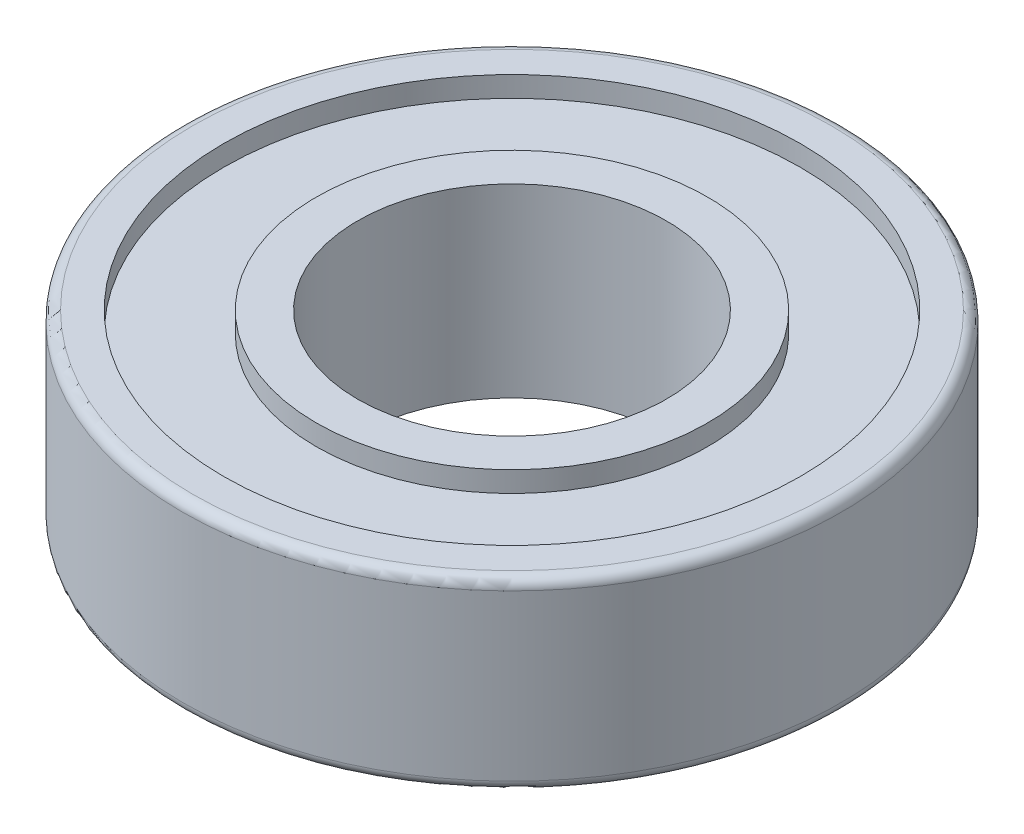
SolidWorks part; units mm, degrees
ref_plane "Plan de face" through (0, 0, 0) normal (0, 0, 1) x (1, 0, 0)
ref_plane "Plan de dessus" through (0, 0, 0) normal (0, 1, 0) x (1, 0, 0)
ref_plane "Plan de droite" through (0, 0, 0) normal (1, 0, 0) x (0, 0, -1)
ref_axis "Axe1" through (0, 4.95, 0) along (0, -1, 0)
sketch "Disque_Intérieur" plane through (0, 0, 0) normal (0, 0, 1) x (1, 0, 0)
  line L1 (7.5, -4.5) -> (9.5, -4.5)
  line L2 (7.5, -4.5) -> (7.5, 4.5)
  line L3 (7.5, 4.5) -> (9.5, 4.5)
  line L4 (9.5, -4.5) -> (9.5, 4.5)
  line L5 (7.5, -4.5) -> (9.5, 4.5) construction
  line L6 (7.5, 4.5) -> (9.5, -4.5) construction
  point P0 (8.5, 0)
  dimension "D1" = 2
  dimension "D2" = 9
  dimension "D3" = 7.5
revolve "Révolution1_Disque_Intérieur" add sketch "Disque_Intérieur" angle 360 about axis through (0, 4.95, 0) along (0, -1, 0)
sketch "Disque_extérieur" plane through (0, 0, 0) normal (0, 0, 1) x (1, 0, 0)
  line L1 (14, -4.5) -> (16, -4.5)
  line L2 (14, -4.5) -> (14, 4.5)
  line L3 (14, 4.5) -> (16, 4.5)
  line L4 (16, -4.5) -> (16, 4.5)
  line L5 (14, -4.5) -> (16, 4.5) construction
  line L6 (14, 4.5) -> (16, -4.5) construction
  line L7 (17.6, 0) -> (-17.6, 0) construction
  line L8 (0, -4.95) -> (0, 4.95) construction
  point P0 (15, 0)
  dimension "D1" = 2
  dimension "D2" = 9
  dimension "D3" = 14
revolve "Révolution2_Disque_extérieur" add sketch "Disque_extérieur" angle 360 about axis through (0, 4.95, 0) along (0, -1, 0)
sketch "Disque_Intermédiaire" plane through (0, 0, 0) normal (0, 0, 1) x (1, 0, 0)
  line L0 (17.6, 0) -> (-17.6, 0) construction
  line L1 (9.5, -3.5) -> (14, -3.5)
  line L2 (9.5, -3.5) -> (9.5, 3.5)
  line L3 (9.5, 3.5) -> (14, 3.5)
  line L4 (14, -3.5) -> (14, 3.5)
  line L5 (9.5, -3.5) -> (14, 3.5) construction
  line L6 (9.5, 3.5) -> (14, -3.5) construction
  line L7 (14, -4.5) -> (14, 4.5) construction
  line L8 (9.5, -4.5) -> (9.5, 4.5) construction
  line L10 (16, 4.5) -> (-16, 4.5) construction
  point P0 (11.75, 0)
  dimension "D1" = 1
revolve "Révolution3_Disque_Intermédiaire" add sketch "Disque_Intermédiaire" angle 360 about axis through (0, 4.95, 0) along (0, -1, 0)
fillet "Congé1_Disque_extérieur_0.5mm" radius 0.5 2 edges at (0, -4.5, 16) (0, 4.5, 16)
